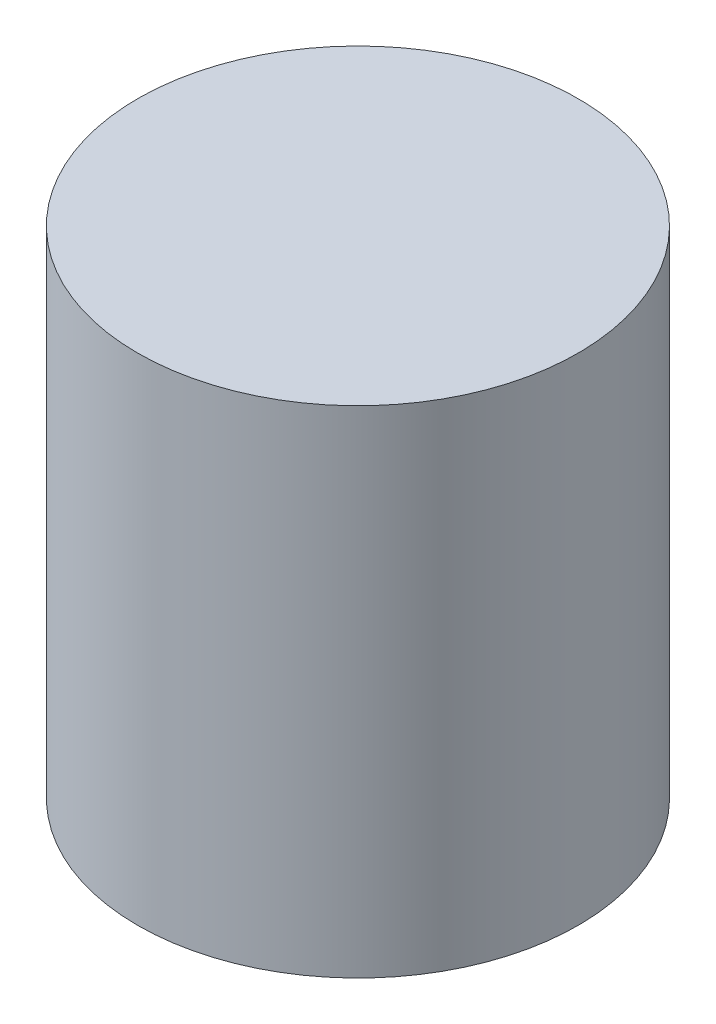
SolidWorks part; units mm, degrees
ref_plane "Спереди" through (0, 0, 0) normal (0, 0, 1) x (1, 0, 0)
ref_plane "Сверху" through (0, 0, 0) normal (0, 1, 0) x (1, 0, 0)
ref_plane "Справа" through (0, 0, 0) normal (1, 0, 0) x (0, 0, -1)
sketch "Эскиз1" plane through (0, 0, 0) normal (0, 1, 0) x (1, 0, 0)
  circle A0 centre (0, 0) radius 21.625
  dimension "D1" = 43.25
extrude "Бобышка-Вытянуть1" add sketch "Эскиз1" along normal blind 48.65
sketch "Эскиз2" plane through (0, 0, 0) normal (0, -1, 0) x (1, 0, 0)
  circle A0 centre (0, 0) radius 19.625
  circle A1 centre (0, 0) radius 21.625 construction
  dimension "D1" = 2
extrude "Вырез-Вытянуть1" cut sketch "Эскиз2" against normal blind 46.65
